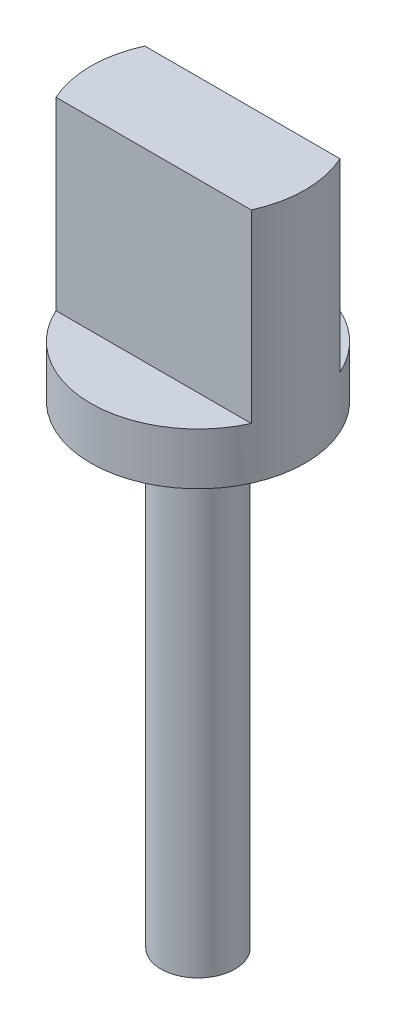
SolidWorks part; units mm, degrees
ref_plane "Alzado" through (0, 0, 0) normal (0, 0, 1) x (1, 0, 0)
ref_plane "Planta" through (0, 0, 0) normal (0, 1, 0) x (1, 0, 0)
ref_plane "Vista lateral" through (0, 0, 0) normal (1, 0, 0) x (0, 0, -1)
sketch "Croquis1" plane through (0, 0, 0) normal (0, 1, 0) x (1, 0, 0)
  circle A0 centre (0, 0) radius 1.45
  dimension "D1" = 2.9
extrude "Saliente-Extruir1" add sketch "Croquis1" along normal blind 10.7
sketch "Croquis2" plane through (0, 10.7, 0) normal (0, 1, 0) x (1, 0, 0)
  line L0 (-1, -1.05) -> (1, -1.05)
  arc A0 (-1, -1.05) -> (1, -1.05) centre (0, 0) ccw
  dimension "D1" = 1.05
extrude "Cortar-Extruir1" cut sketch "Croquis2" against normal blind 6
sketch "Croquis3" plane through (0, 0, 0) normal (0, -1, 0) x (1, 0, 0)
  circle A0 centre (0, 0) radius 0.5
  dimension "D1" = 1
extrude "Saliente-Extruir2" add sketch "Croquis3" along normal blind 6.4
sketch "Sketch1" plane through (0, 10.7, 0) normal (0, 1, 0) x (1, 0, 0)
  line L0 (-1.9428, 0.6) -> (1.9428, 0.6)
  line L1 (-1.6219, 0) -> (1.843, 0) construction
  line L4 (-1.9428, -0.6) -> (1.9428, -0.6)
  arc A1 (1.9428, 0.6) -> (-1.9428, 0.6) centre (0, 0) ccw
  arc A2 (-1.9428, -0.6) -> (1.9428, -0.6) centre (0, 0) ccw
  dimension "D1" = 1.2
extrude "Cut-Extrude1" cut sketch "Sketch1" against normal up to surface (10 mm away)
sketch "Sketch2" plane through (0, 0, 0.6) normal (0, 0, 1) x (1, 0, 0)
  line L0 (-1.32, 0.7) -> (1.32, 0.7) construction
  line L1 (-3.1473, 12.0985) -> (3.5936, 12.0985)
  line L2 (-3.1473, 12.0985) -> (-3.1473, 3.2)
  line L3 (-3.1473, 3.2) -> (3.5936, 3.2)
  line L4 (3.5936, 12.0985) -> (3.5936, 3.2)
  dimension "D1" = 2.5
extrude "Cut-Extrude2" cut sketch "Sketch2" against normal through all
